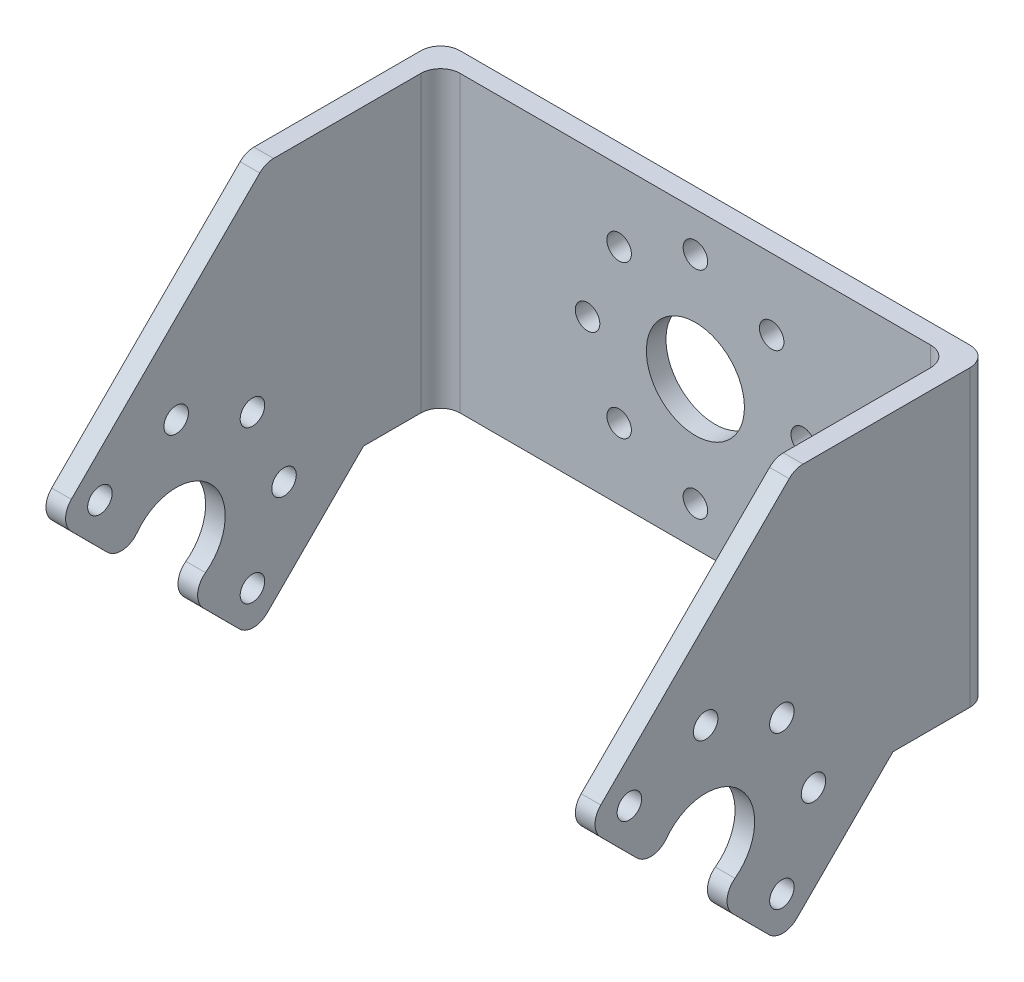
SolidWorks part; units mm, degrees
ref_plane "Plano frontal" through (0, 0, 0) normal (0, 0, 1) x (1, 0, 0)
ref_plane "Plano superior" through (0, 0, 0) normal (0, 1, 0) x (1, 0, 0)
ref_plane "Plano direito" through (0, 0, 0) normal (1, 0, 0) x (0, 0, -1)
sketch "Esboço1" plane through (0, 0, 0) normal (0, 0, 1) x (1, 0, 0)
  line L1 (-28, -15) -> (28, -15)
  line L2 (-28, -15) -> (-28, 15)
  line L3 (-28, 15) -> (28, 15)
  line L4 (28, -15) -> (28, 15)
  line L5 (-28, -15) -> (28, 15) construction
  line L6 (-28, 15) -> (28, -15) construction
  point P0 (0, 0)
  dimension "D1" = 56
  dimension "D2" = 30
extrude "Ressalto-extrusão1" add sketch "Esboço1" against normal blind 2
sketch "Esboço2" plane through (28, 0, 0) normal (1, 0, 0) x (0, 0, -1)
  line L0 (0, 15) -> (-17.0216, 15)
  line L1 (-18.4358, 14.4142) -> (-37.6511, -4.8011)
  line L2 (0, -15) -> (-7.85, -15)
  line L3 (-7.85, -15) -> (-17.6767, -24.8267)
  line L4 (-37.6532, -7.6274) -> (-20.5072, -24.8246)
  line L5 (0, 15) -> (0, -15)
  arc A0 (-18.4358, 14.4142) -> (-17.0216, 15) centre (-17.0216, 13) cw
  arc A1 (-20.5072, -24.8246) -> (-17.6767, -24.8267) centre (-19.0909, -23.4125) ccw
  arc A2 (-37.6532, -7.6274) -> (-37.6511, -4.8011) centre (-36.2369, -6.2153) cw
  point P6 (-17.85, 15)
  point P14 (-19.093, -26.243)
  point P17 (-39.0632, -6.2132)
  dimension "D4" = 2
  dimension "D7" = 2
  dimension "D1" = 17.85
  dimension "D2" = 30
  dimension "D3" = 135
  dimension "D5" = 7.85
  dimension "D6" = 13.897
extrude "Ressalto-extrusão2" add sketch "Esboço2" against normal blind 2
sketch "Esboço3" plane through (28, 0, 0) normal (1, 0, 0) x (0, 0, -1)
  line L0 (-37.6532, -7.6274) -> (-20.5072, -24.8246) construction
  line L1 (-17.6767, -24.8267) -> (-7.85, -15) construction
  circle A0 centre (-26.9553, -14.1083) radius 5
  dimension "D1" = 10
  dimension "D2" = 3
  dimension "D3" = 14.14
extrude "Corte-extrusão1" cut sketch "Esboço3" against normal blind 2
fillet "Filete1" radius 2 2 edges at (27, -19.0591, 26.2555) (27, -13.3938, 31.904)
sketch "Esboço4" plane through (28, 0, 0) normal (1, 0, 0) x (0, 0, -1)
  line L0 (-26.9553, -14.1083) -> (-34.7334, -6.3301) construction
  line L1 (-18.4358, 14.4142) -> (-37.6511, -4.8011) construction
  circle A1 centre (-34.7334, -6.3301) radius 1.25
  dimension "D2" = 2.5
  dimension "D1" = 11
  dimension "D3" = 90
extrude "Corte-extrusão2" cut sketch "Esboço4" against normal blind 2
pattern_circular "PadrãoCircular1" count 5 every 45 about axis through (0, -14.1083, 26.9553) along (1, 0, 0) of "Corte-extrusão2"
mirror "Espelhar3" about plane through (0, 0, 0) normal (1, 0, 0) of "PadrãoCircular1", "Corte-extrusão2", "Filete1", "Corte-extrusão1", "Ressalto-extrusão2"
fillet "Filete3" radius 2 4 edges at (-26, 0, 0) (26, 0, 0) (28, 0, -2) (-28, 0, -2)
sketch "Esboço5" plane through (0, 0, 0) normal (0, 0, 1) x (1, 0, 0)
  circle A0 centre (0, 0) radius 5
  dimension "D1" = 10
extrude "Corte-extrusão3" cut sketch "Esboço5" against normal blind 2
sketch "Esboço6" plane through (0, 0, 0) normal (0, 0, 1) x (1, 0, 0)
  line L0 (0, 0) -> (0, 11) construction
  circle A0 centre (0, 11) radius 1.25
  dimension "D2" = 2.5
  dimension "D1" = 11
extrude "Corte-extrusão4" cut sketch "Esboço6" against normal blind 2
pattern_circular "PadrãoCircular2" count 8 over 360 about axis through (0, 0, 0) along (0, 0, 1) of "Corte-extrusão4", "Corte-extrusão3"
